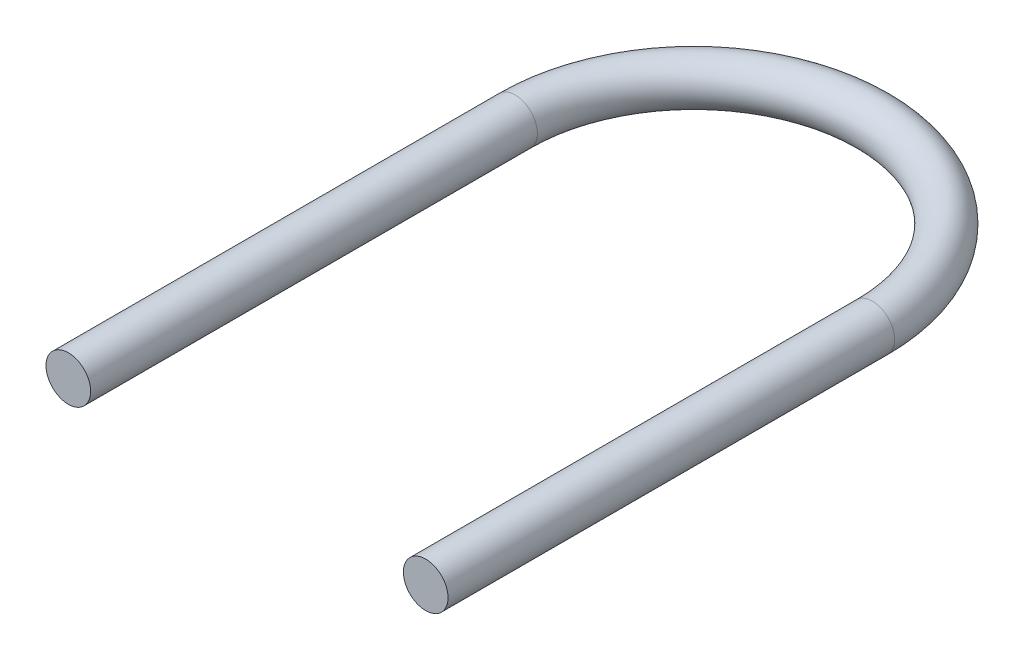
SolidWorks part; units mm, degrees
ref_plane "Front Plane" through (0, 0, 0) normal (0, 0, 1) x (1, 0, 0)
ref_plane "Top Plane" through (0, 0, 0) normal (0, 1, 0) x (1, 0, 0)
ref_plane "Right Plane" through (0, 0, 0) normal (1, 0, 0) x (0, 0, -1)
sketch "Sketch1" plane through (0, 0, 0) normal (0, 0, 1) x (1, 0, 0)
  circle A0 centre (0, 0) radius 12.7
  dimension "D1" = 25.4
sketch "Sketch2" plane through (0, 0, 0) normal (0, 1, 0) x (1, 0, 0)
  line L0 (0, 0) -> (0, 254)
  line L1 (203.2, 254) -> (203.2, 0)
  arc A0 (0, 254) -> (203.2, 254) centre (101.6, 254) cw
  dimension "D2" = 101.6
  dimension "D1" = 254
  dimension "D3" = 254
sweep "Sweep2" add profiles "Sketch1" path "Sketch2"
